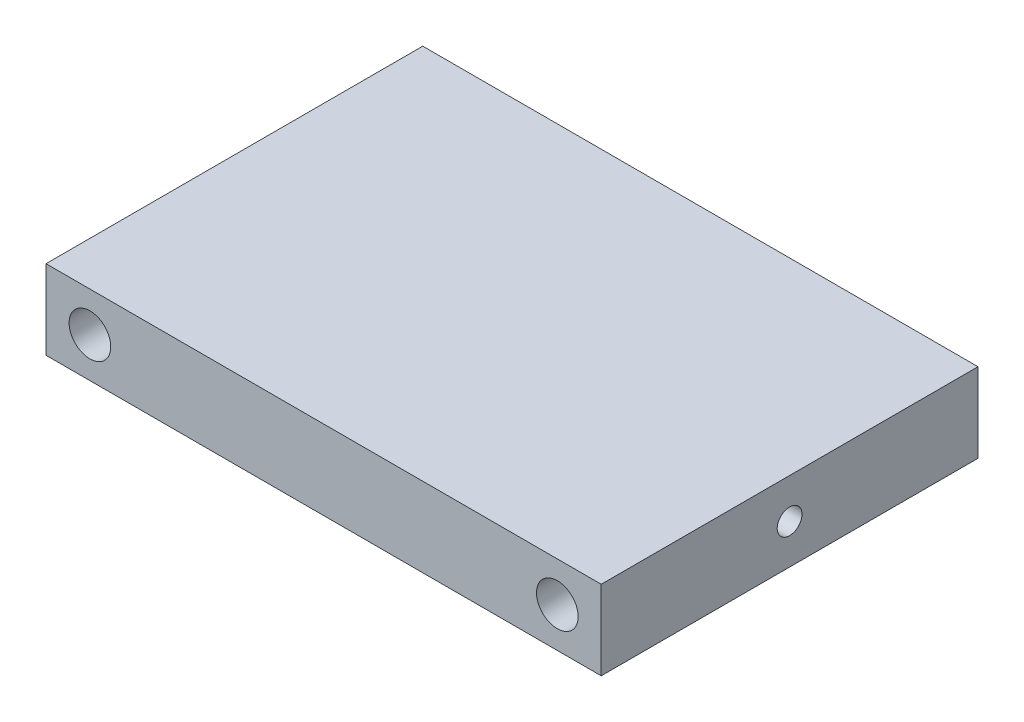
SolidWorks part; units mm, degrees
ref_plane "Спереди" through (0, 0, 0) normal (0, 0, 1) x (1, 0, 0)
ref_plane "Сверху" through (0, 0, 0) normal (0, 1, 0) x (1, 0, 0)
ref_plane "Справа" through (0, 0, 0) normal (1, 0, 0) x (0, 0, -1)
sketch "Эскиз1" plane through (0, 0, 0) normal (0, 0, 1) x (1, 0, 0)
  line L1 (0, 0) -> (56, 0)
  line L2 (0, 0) -> (0, 8)
  line L3 (0, 8) -> (56, 8)
  line L4 (56, 0) -> (56, 8)
  dimension "D1" = 56
  dimension "D2" = 8
extrude "Бобышка-Вытянуть1" add sketch "Эскиз1" along normal blind 38
sketch "Эскиз2" plane through (0, 0, 38) normal (0, 0, 1) x (1, 0, 0)
  line L0 (0, 8) -> (0, 0) construction
  line L1 (56, 8) -> (0, 8) construction
  circle A0 centre (4.43, 4) radius 2.1
  circle A1 centre (51.57, 4) radius 2.1
  point P4 (0, 4)
  point P7 (28, 8)
  dimension "D1" = 4.2
  dimension "D2" = 0
  dimension "D3" = 23.57
  dimension "D4" = 2
extrude "Вырез-Вытянуть1" cut sketch "Эскиз2" against normal through all
sketch "Эскиз3" plane through (56, 0, 0) normal (1, 0, 0) x (0, 0, -1)
  line L0 (-38, 8) -> (0, 8) construction
  line L1 (-38, 0) -> (-38, 8) construction
  circle A0 centre (-19, 4) radius 1.25
  point P4 (-19, 8)
  point P7 (-38, 4)
  dimension "D3" = 2.5
  dimension "D1" = 0
  dimension "D2" = 0
extrude "Вырез-Вытянуть2" cut sketch "Эскиз3" against normal blind 20
